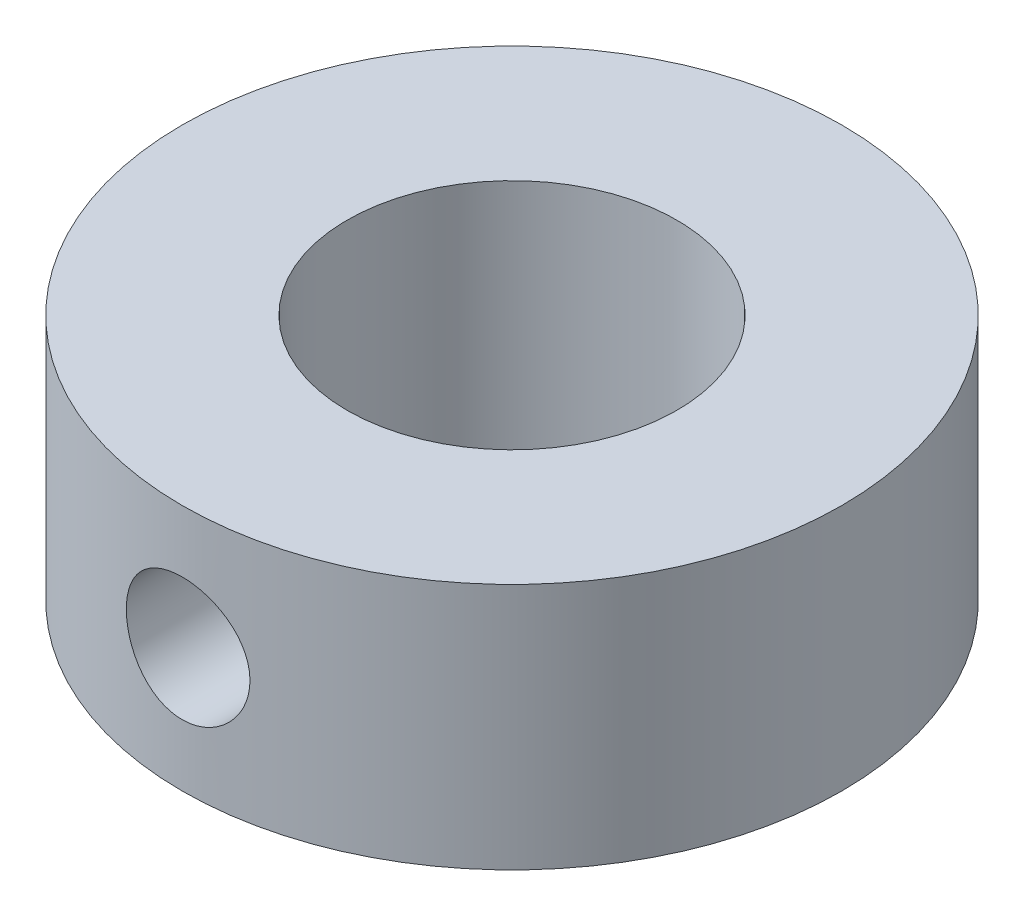
SolidWorks part; units mm, degrees
ref_plane "Front Plane" through (0, 0, 0) normal (0, 0, 1) x (1, 0, 0)
ref_plane "Top Plane" through (0, 0, 0) normal (0, 1, 0) x (1, 0, 0)
ref_plane "Right Plane" through (0, 0, 0) normal (1, 0, 0) x (0, 0, -1)
sketch "Sketch1" plane through (0, 0, 0) normal (0, 1, 0) x (1, 0, 0)
  circle A0 centre (0, 0) radius 12.7
  circle A1 centre (0, 0) radius 6.35
  dimension "D1" = 25.4
  dimension "D2" = 12.7
extrude "Boss-Extrude1" add sketch "Sketch1" along normal blind 9.525
sketch "Sketch2" plane through (0, 0, 0) normal (0, 0, 1) x (1, 0, 0)
  line L0 (-12.7, 9.525) -> (-12.7, 0) construction
  line L1 (-12.7, 4.7625) -> (0, 4.7625) construction
  circle A0 centre (0, 4.7625) radius 2.3813
  dimension "D1" = 4.7625
extrude "Cut-Extrude1" cut sketch "Sketch2" along normal through all
